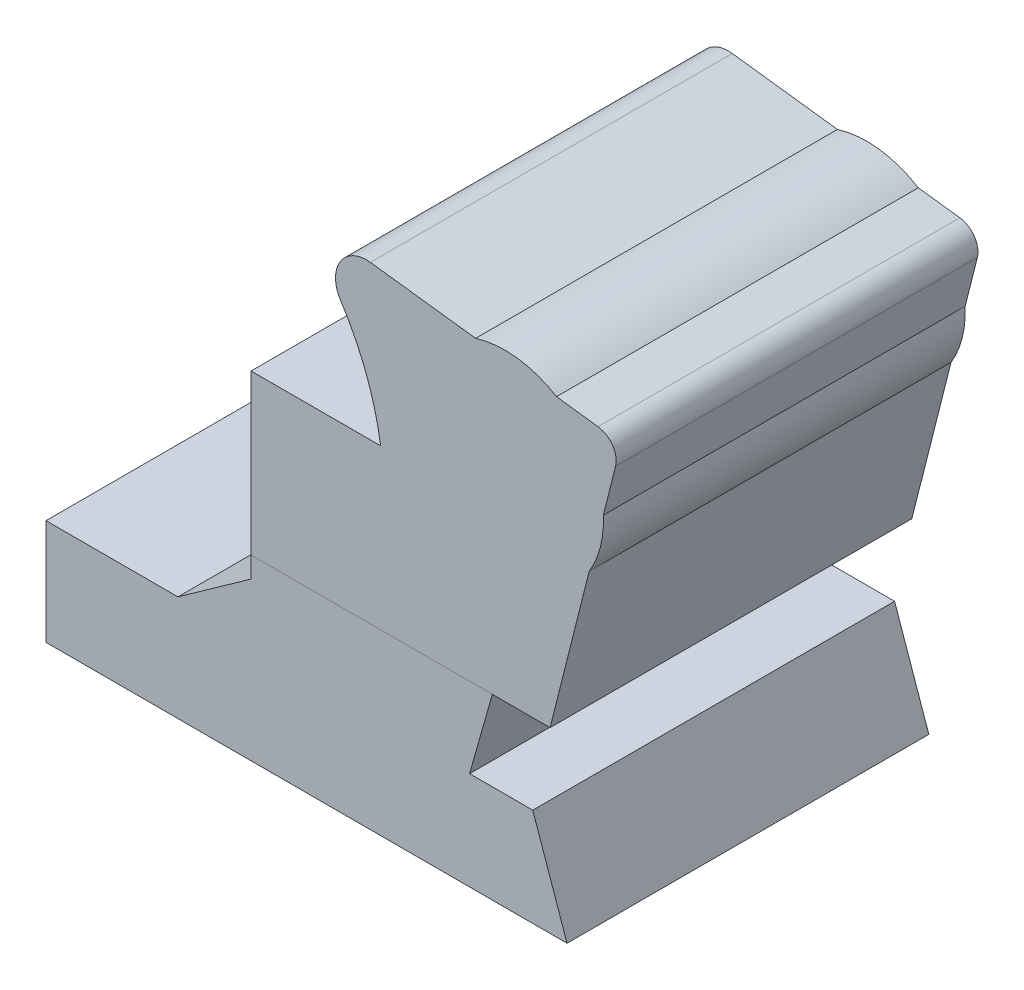
SolidWorks part; units mm, degrees
ref_plane "前视基准面" through (0, 0, 0) normal (0, 0, 1) x (1, 0, 0)
ref_plane "上视基准面" through (0, 0, 0) normal (0, 1, 0) x (1, 0, 0)
ref_plane "右视基准面" through (0, 0, 0) normal (1, 0, 0) x (0, 0, -1)
other "Configuration Table"
sketch "草图1" plane through (0, 0, 0) normal (0, 0, 1) x (1, 0, 0)
  line L0 (36.476, 29.1479) -> (56.672, 43.5041)
  line L1 (56.672, 93.3075) -> (92.4962, 93.3075)
  line L4 (0, 0) -> (144.001, 0)
  line L5 (144.001, 0) -> (134.5299, 27.1222)
  line L6 (117.0722, 27.1222) -> (123.3535, 49.2574)
  line L7 (134.5299, 27.1222) -> (117.0722, 27.1222)
  line L12 (0, 0) -> (0, 29.1479)
  line L16 (152.5757, 127.9319) -> (89.661, 135.7982)
  line L17 (88.5965, 127.2845) -> (126.841, 106.1775)
  line L20 (123.3535, 49.2574) -> (139.3032, 49.2574)
  line L22 (139.3032, 49.2574) -> (157.4114, 120.8535)
  line L23 (0, 29.1479) -> (36.476, 29.1479)
  line L26 (89.661, -27.3497) -> (89.661, 97.7464) construction
  line L27 (56.672, 43.5041) -> (56.672, 93.3075)
  arc A2 (92.4962, 93.3075) -> (81.3935, 122.6226) centre (18.9675, 82.2197) ccw
  arc A7 (157.4114, 120.8535) -> (152.5757, 127.9319) centre (151.866, 122.2561) ccw
  arc A8 (81.3935, 122.6226) -> (89.661, 135.7982) centre (88.5965, 127.2845) cw
  circle A15 centre (126.841, 106.1775) radius 27.2182
  point P0 (0, 0)
  dimension "D2" = 54.4365
  dimension "D3" = 74.36
  dimension "D4" = 5.72
  dimension "D5" = 8.58
  dimension "D1" = 106.1775
  dimension "D6" = 18.9675
  dimension "D7" = 36.476
  dimension "D8" = 56.672
  dimension "D9" = 81.3935
  dimension "D10" = 89.661
  dimension "D11" = 151.866
  dimension "D12" = 92.4962
  dimension "D13" = 117.0722
  dimension "D14" = 123.3535
  dimension "D15" = 126.841
  dimension "D16" = 134.5299
  dimension "D17" = 139.3032
  dimension "D18" = 144.001
  dimension "D19" = 27.1222
  dimension "D20" = 29.1479
  dimension "D21" = 157.4114
  dimension "D22" = 43.5041
  dimension "D23" = 49.2574
extrude "凸台-拉伸1" add sketch "草图1" along normal mid plane 100 contours A2 A8 L16 A7 L22 L20 L6 L7 L5 L4 L12 L23 L0 L27 L1 | A15
sketch "草图2" plane through (0, 0, 50) normal (0, 0, 1) x (1, 0, 0)
  line L0 (123.3535, 49.2574) -> (56.672, 49.2574)
  line L1 (56.672, 43.5041) -> (56.672, 93.3075) construction
split "分割1" trim tools "草图2" bodies to split 106 resulting bodies 107 108
